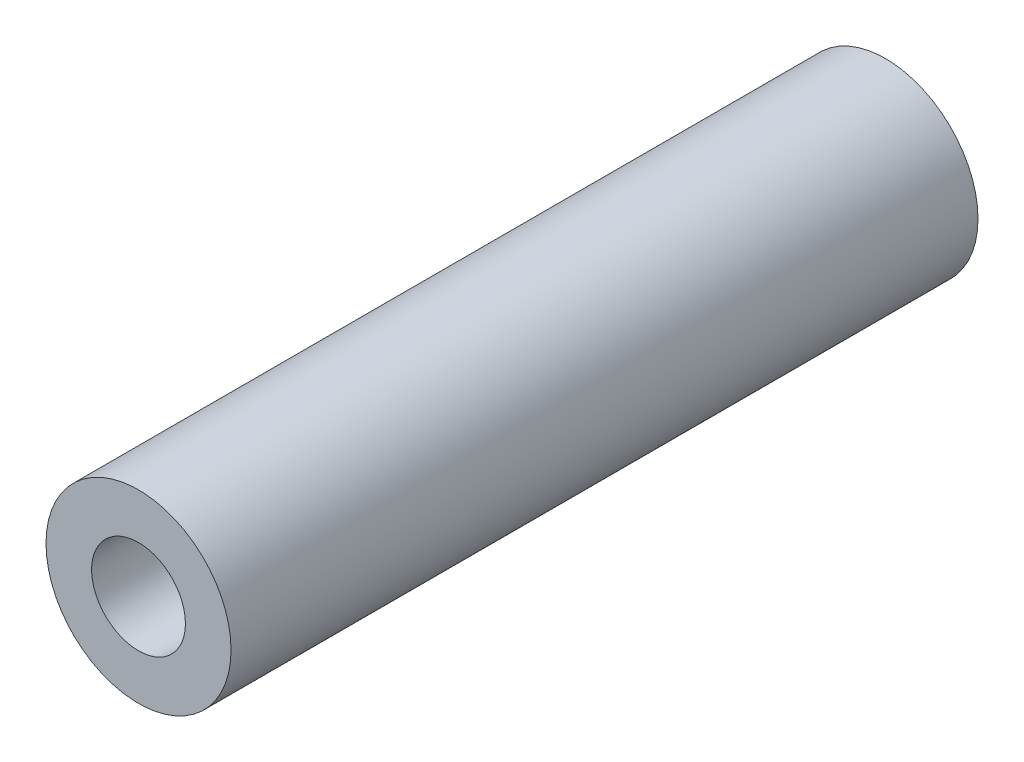
SolidWorks part; units mm, degrees
ref_plane "Plan de face" through (0, 0, 0) normal (1, 0, 0) x (0, 1, 0)
ref_plane "Plan de dessus" through (0, 0, 0) normal (0, 0, 1) x (0, 1, 0)
ref_plane "Plan de droite" through (0, 0, 0) normal (0, 1, 0) x (-1, 0, 0)
sketch "Esquisse1" plane through (0, 0, 0) normal (0, 0, 1) x (0, 1, 0)
  circle A0 centre (0, 0) radius 4
  circle A1 centre (0, 0) radius 7.89
  dimension "D1" = 15.78
  dimension "D2" = 8
extrude "Boss.-Extru.1" add sketch "Esquisse1" along normal blind 63.7
